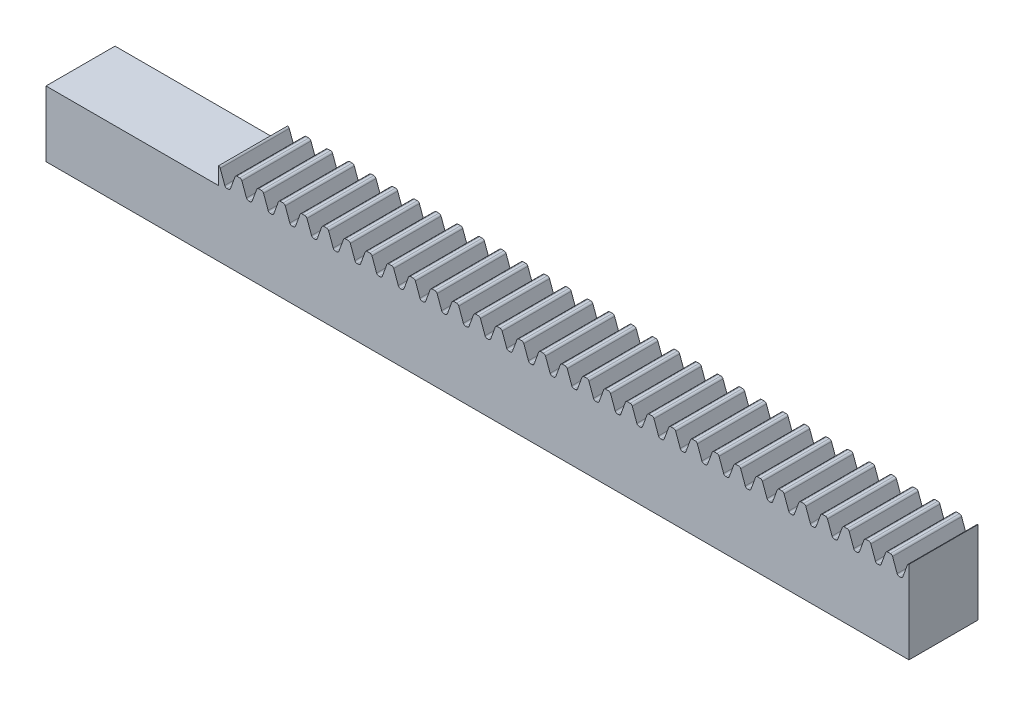
SolidWorks part; units mm, degrees
material "AISI 1045 Steel, cold drawn"
ref_plane "Front Plane" through (0, 0, 0) normal (0, 0, 1) x (1, 0, 0)
ref_plane "Top Plane" through (0, 0, 0) normal (0, 1, 0) x (1, 0, 0)
ref_plane "Right Plane" through (0, 0, 0) normal (1, 0, 0) x (0, 0, -1)
sketch "Sketch1" plane through (0, 0, 0) normal (0, 0, 1) x (1, 0, 0)
  line L0 (-50, 6) -> (-50, -6) construction
  line L1 (-50, -6) -> (50, -6) construction
  line L2 (50, -6) -> (50, 6) construction
  line L4 (0, 6) -> (0, -6) construction
  line L5 (-50, 5) -> (50, 5) construction
  line L6 (-47.5453, 6) -> (-46.7025, 6) construction
  line L7 (-46.7025, 6) -> (-45.8835, 3.75) construction
  line L8 (-47.5453, 6) -> (-48.3643, 3.75) construction
  line L9 (-48.3643, 3.75) -> (-45.8835, 3.75) construction
  line L10 (-47.1239, 6) -> (-47.1239, 3.75) construction
  line L11 (-50, 0) -> (-40.8407, 0) construction
  line L12 (50, 0) -> (40.8407, 0) construction
  point P15 (-43.9823, 6)
  point P16 (-15.5, -6)
  point P17 (-46.3385, 5)
  point P18 (-47.9093, 5)
  point P21 (-0.5, -6)
  dimension "Length" = 100
  dimension "Height" = 12
  dimension "Approximate Number of Teeth" = 31
  dimension "Pressure Angle" = 20
  dimension "Circular Pitch" = 3.1416
  dimension "Addendum" = 1
  dimension "Dedendum" = 1.25
  dimension "Circular Tooth Thickness" = 1.5708
  dimension "Module" = 1
  dimension "Rack Length" = 94.2478
  dimension "D1" = 6.2832
sketch "Sketch2" plane through (0, 0, 0) normal (1, 0, 0) x (0, 0, -1)
  line L0 (-5, 0) -> (5, 0) construction
  dimension "Face Width" = 10
sketch "Sketch3" plane through (0, 0, 0) normal (0, 0, 1) x (1, 0, 0)
  line L1 (-50, 6) -> (50, 6)
  line L2 (-50, 6) -> (-50, -6)
  line L3 (-50, -6) -> (50, -6)
  line L4 (50, 6) -> (50, -6)
extrude "Boss-Extrude1" add sketch "Sketch3" against normal up to vertex (5 mm away) and the other way up to vertex (5 mm away) up to point (0, 0, -5) other way up to point (0, 0, 5)
sketch "Sketch4" plane through (0, 0, 0) normal (0, 0, 1) x (1, 0, 0)
  line L0 (-47.1239, 6) -> (-43.9823, 6) construction
  line L9 (-45.5531, 6) -> (-45.5531, 3.75)
  line L10 (-45.5531, 3.75) -> (-45.8835, 3.75)
  line L11 (-45.8835, 3.75) -> (-46.7025, 6)
  line L12 (-46.7025, 6) -> (-45.5531, 6)
  line L13 (-47.5453, 6) -> (-48.3643, 3.75)
  line L14 (-48.3643, 3.75) -> (-48.6947, 3.75)
  line L15 (-48.6947, 3.75) -> (-48.6947, 6)
  line L16 (-48.6947, 6) -> (-47.5453, 6)
  line L17 (50, 6) -> (-50, 6) construction
  line L18 (-47.5453, 6) -> (-47.3104, 6)
  line L19 (-46.9374, 6) -> (-46.7025, 6)
  arc A0 (-48.5992, 3.75) -> (-48.2839, 3.9708) centre (-48.5992, 4.0855) ccw
  arc A1 (-45.9639, 3.9708) -> (-45.6486, 3.75) centre (-45.6486, 4.0855) ccw
  arc A2 (-47.6257, 5.7792) -> (-47.3104, 6) centre (-47.3104, 5.6645) cw
  arc A3 (-46.9374, 6) -> (-46.6221, 5.7792) centre (-46.9374, 5.6645) cw
  dimension "D1" = 0.3355
extrude "Cut-Extrude1" cut sketch "Sketch4" against normal through all both and the other way through all contours L14 A0 L13 L16 L15 | L13 A2 L18 | L19 A3 L11 | L11 A1 L10 L9 L12
pattern_linear "LPattern1" count 32 spacing 3.1416 along (1, 0, 0) count 2 spacing 3.1416 along (-1, 0, 0) of "Cut-Extrude1"
sketch "Drawing Refernce 1" plane through (0, 0, 5) normal (0, 0, 1) x (1, 0, 0)
  line L0 (-50, 0) -> (50, 0) construction
  point P6 (-35, 0)
  point P7 (-27.5, 0)
  point P8 (35, 0)
  dimension "D1" = 15
  dimension "D2" = 22.5
  dimension "D3" = 15
sketch "Sketch6" plane through (-50, 0, 0) normal (-1, 0, 0) x (0, 0, 1)
  line L0 (5, 5.9906) -> (5, -6) construction
  line L1 (-5, -6) -> (5, -6)
  line L2 (-5, -6) -> (-5, 3.5)
  line L3 (-5, 3.5) -> (5, 3.5)
  line L4 (5, -6) -> (5, 3.5)
  dimension "D1" = 9.5
extrude "Boss-Extrude3" add sketch "Sketch6" along normal blind 25
equation "\"Diametral Pitch\"= 1"
equation "\"Pressure Angle\"=20"
equation "\"Dedendum\"= 1.25 / \"Diametral Pitch\""
equation "\"Addendum\"= 1 / \"Diametral Pitch\""
equation "\"WorkingDepth\"= 2 / \"Diametral Pitch\""
equation "\"WholeDepth\"= 2.25 / \"Diametral Pitch\""
equation "\"Clearance\"= 0.25 / \"Diametral Pitch\""
equation "\"ToothThickness\"= ( pi / 2 ) / \"Diametral Pitch\""
equation "\"CircularPitch\"= pi / \"Diametral Pitch\""
equation "\"Fillet\"= \"Clearance\" * cos ( \"Pressure Angle\" ) * tan ( ( 90 + \"Pressure Angle\" ) / 2 )"
equation "\"Module\"= 1"
equation "\"Addendum@Sketch1\"=\"Addendum\""
equation "\"Pressure Angle@Sketch1\"=\"Pressure Angle\""
equation "\"Dedendum@Sketch1\"=\"Dedendum\""
equation "\"Circular Pitch@Sketch1\"=\"CircularPitch\""
equation "\"Circular Tooth Thickness@Sketch1\"=\"ToothThickness\""
equation "\"Module@Sketch1\"=\"Module\""
equation "\"Approximate Number of Teeth@Sketch1\" = int ( \"Length@Sketch1\" /  ( 2 * \"Circular Tooth Thickness@Sketch1\" )  ) "
equation "\"Rack Length@Sketch1\" = \"Circular Pitch@Sketch1\" *  ( \"Approximate Number of Teeth@Sketch1\" - 1 ) "
equation "\"D3@LPattern1\"=\"CircularPitch\""
equation "\"D1@LPattern1\"=\"Approximate Number of Teeth@Sketch1\"+1"
equation "\"D1@Sketch1\"=\"Circular Pitch@Sketch1\"*2"
equation "\"D1@Sketch4\"=\"Fillet\""
equation "\"D4@LPattern1\"=\"CircularPitch\""
equation "\"D2@Drawing Refernce 1\"=\"D1@Drawing Refernce 1\"*1.5"
equation "\"D3@Drawing Refernce 1\"=\"D1@Drawing Refernce 1\""
